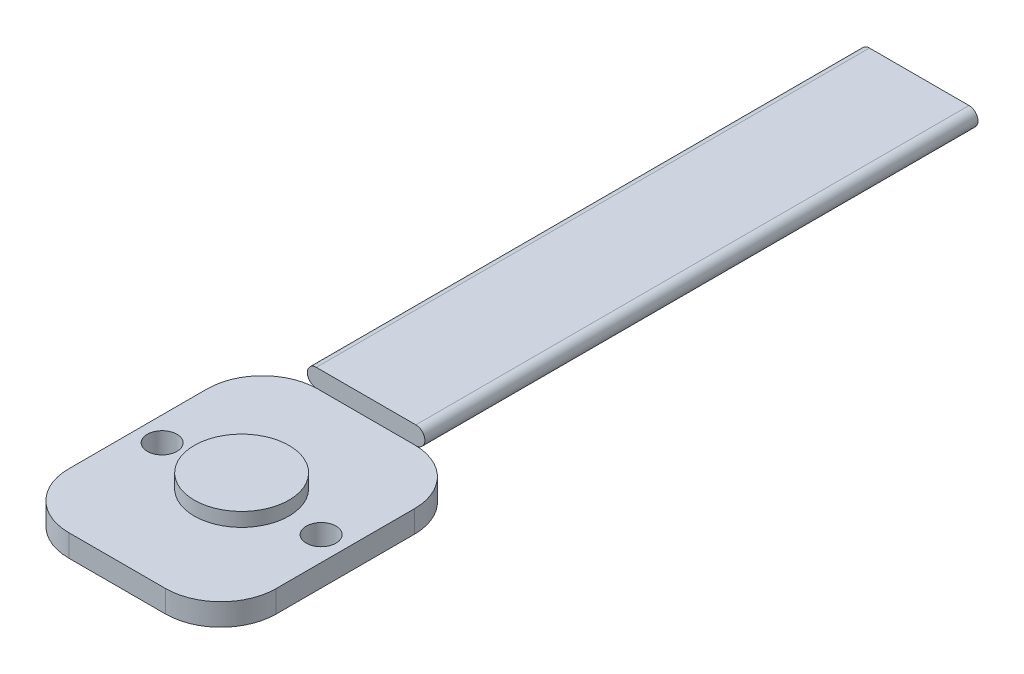
SolidWorks part; units mm, degrees
ref_plane "Front Plane" through (0, 0, 0) normal (0, 0, 1) x (1, 0, 0)
ref_plane "Top Plane" through (0, 0, 0) normal (0, 1, 0) x (1, 0, 0)
ref_plane "Right Plane" through (0, 0, 0) normal (1, 0, 0) x (0, 0, -1)
sketch "Sketch1" plane through (0, 0, 0) normal (0, 1, 0) x (1, 0, 0)
  line L0 (-3.5, 9) -> (3.5, 9)
  line L1 (7.5, 5) -> (7.5, -5)
  line L2 (3.5, -9) -> (-3.5, -9)
  line L3 (-7.5, -5) -> (-7.5, 5)
  line L4 (-7.5, 9) -> (7.5, -9) construction
  line L5 (-5.75, 0) -> (5.75, 0) construction
  arc A0 (-3.5, -9) -> (-7.5, -5) centre (-3.5, -5) cw
  arc A1 (7.5, -5) -> (3.5, -9) centre (3.5, -5) cw
  arc A2 (7.5, 5) -> (3.5, 9) centre (3.5, 5) ccw
  arc A3 (-3.5, 9) -> (-7.5, 5) centre (-3.5, 5) ccw
  circle A4 centre (-5.75, 0) radius 1.075
  circle A5 centre (5.75, 0) radius 1.075
  point P12 (7.5, 9)
  dimension "D3" = 4
  dimension "D4" = 2.15
  dimension "D1" = 15
  dimension "D2" = 18
  dimension "D5" = 11.5
extrude "Boss-Extrude1" add sketch "Sketch1" along normal blind 1.6
sketch "Sketch2" plane through (0, 1.6, 0) normal (0, 1, 0) x (1, 0, 0)
  circle A0 centre (0, 0) radius 3.4265
extrude "Boss-Extrude2" add sketch "Sketch2" along normal blind 1
sketch "Sketch4" plane through (0, 0, -9) normal (0, 0, -1) x (-1, 0, 0)
  line L0 (3.6, 2.25) -> (-3.6, 2.25) construction
  line L1 (3.6, 1.6) -> (-3.6, 1.6)
  line L2 (3.6, 2.9) -> (-3.6, 2.9)
  line L3 (0, 0) -> (0, 2.25) construction
  line L5 (-3.5, 1.6) -> (3.5, 1.6) construction
  arc A0 (3.6, 1.6) -> (3.6, 2.9) centre (3.6, 2.25) ccw
  arc A1 (-3.6, 2.9) -> (-3.6, 1.6) centre (-3.6, 2.25) ccw
  point P2 (0, 2.25)
  point P10 (0, 1.6)
  point P13 (0, 0)
  dimension "D1" = 7.2
  dimension "D2" = 1.3
extrude "Boss-Extrude3" add sketch "Sketch4" along normal blind 40 separate body
